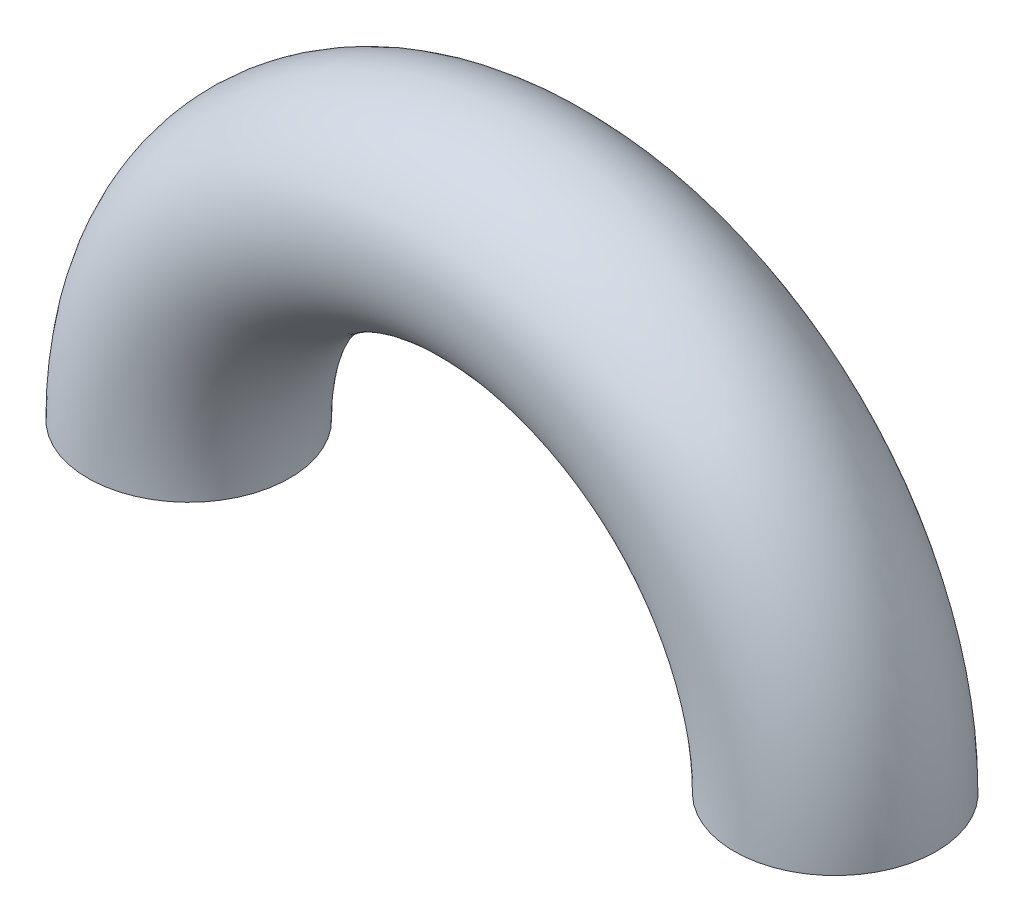
SolidWorks part; units mm, degrees
ref_plane "Front Plane" through (0, 0, 0) normal (0, 0, 1) x (1, 0, 0)
ref_plane "Top Plane" through (0, 0, 0) normal (0, 1, 0) x (1, 0, 0)
ref_plane "Right Plane" through (0, 0, 0) normal (1, 0, 0) x (0, 0, -1)
sketch "Sketch1" plane through (0, 0, 0) normal (0, 1, 0) x (1, 0, 0)
  circle A0 centre (0, 0) radius 1.5875
  point P5 (0, 0)
  dimension "D1" = 3.175
sketch "Sketch2" plane through (0, 0, 0) normal (0, 0, 1) x (1, 0, 0)
  line L1 (0, 0) -> (0, 5.465) construction
  arc A0 (0, 0) -> (10.16, 0) centre (5.08, 0) cw
  point P4 (0, 0)
  point P5 (0, 0)
  point P6 (2.4371, 5.0464)
  point P9 (0, 0)
  point P11 (0, 0)
  point P12 (0, 0)
  dimension "D2" = 10.16
sweep "Sweep1" add profiles "Sketch1" path "Sketch2"
